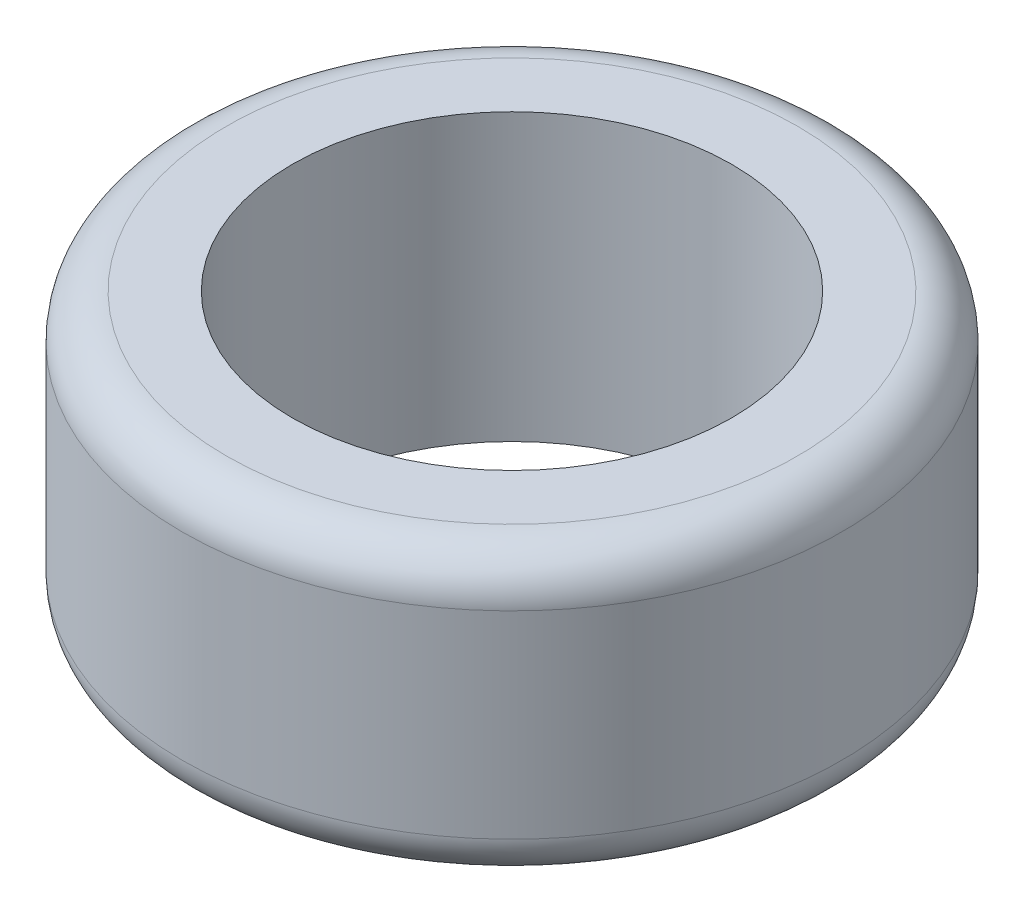
SolidWorks part; units mm, degrees
ref_plane "Front Plane" through (0, 0, 0) normal (0, 0, 1) x (1, 0, 0)
ref_plane "Top Plane" through (0, 0, 0) normal (0, 1, 0) x (1, 0, 0)
ref_plane "Right Plane" through (0, 0, 0) normal (1, 0, 0) x (0, 0, -1)
sketch "Sketch2" plane through (0, 0, 0) normal (0, 1, 0) x (1, 0, 0)
  circle A0 centre (0, 0) radius 15
  circle A1 centre (0, 0) radius 10
  dimension "D1" = 30
  dimension "D2" = 5
extrude "Boss-Extrude1" add sketch "Sketch2" along normal blind 13
fillet "Fillet1" radius 2 2 edges at (0, 0, 15) (0, 13, 15)
